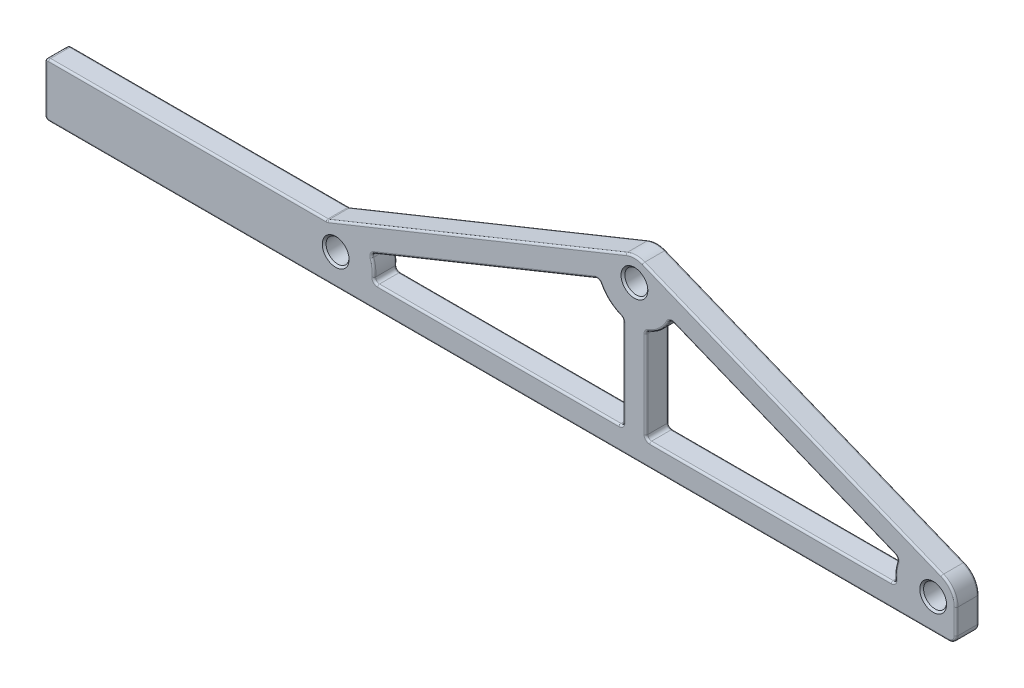
SolidWorks part; units mm, degrees
ref_plane "Plano frontal" through (0, 0, 0) normal (0, 0, 1) x (1, 0, 0)
ref_plane "Plano superior" through (0, 0, 0) normal (0, 1, 0) x (1, 0, 0)
ref_plane "Plano direito" through (0, 0, 0) normal (1, 0, 0) x (0, 0, -1)
sketch "Esboço1" plane through (0, 0, 0) normal (0, 0, 1) x (1, 0, 0)
  line L0 (-2.2496, 5.5623) -> (-80.2496, -25.9832)
  line L1 (2.2496, 5.5623) -> (80.2496, -25.9832)
  line L2 (84, -27.5) -> (-84, -27.5) construction
  line L3 (0, 0) -> (0, -27.5) construction
  line L4 (-78, -32) -> (78, -32) construction
  line L5 (0, -32) -> (0, -27.5) construction
  line L6 (-82, -40.0442) -> (-153.9281, -40.0442)
  line L7 (-82, -40.0442) -> (82, -40.0442)
  line L8 (84, -31.5455) -> (84, -38.0442)
  line L9 (-153.9281, -40.0442) -> (-153.9281, -25.9832)
  line L10 (-153.9281, -25.9832) -> (-80.2496, -25.9832)
  circle A0 centre (0, 0) radius 3
  arc A1 (2.2496, 5.5623) -> (-2.2496, 5.5623) centre (0, 0) ccw
  arc A2 (80.2496, -25.9832) -> (84, -31.5455) centre (78, -31.5455) cw
  arc A4 (82, -40.0442) -> (84, -38.0442) centre (82, -38.0442) ccw
  circle A6 centre (-78, -32) radius 3
  circle A7 centre (78, -32) radius 3
  point P20 (-84, -40.0442)
  dimension "D1" = 6
  dimension "D2" = 12
  dimension "D6" = 6
  dimension "D7" = 2
  dimension "D3" = 168
  dimension "D4" = 12.5442
  dimension "D5" = 27.5
  dimension "D8" = 32
  dimension "D9" = 156
extrude "Ressalto-extrusão1" add sketch "Esboço1" along normal mid plane 6
chamfer "Chanfro1" distance 0.5 angle 45 6 edges at (81, -32, -3) (81, -32, 3) (3, 0, -3) (3, 0, 3) (-75, -32, -3) (-75, -32, 3)
sketch "Esboço2" plane through (0, 0, 0) normal (0, 0, 1) x (1, 0, 0)
  line L0 (-2.2496, 5.5623) -> (-80.2496, -25.9832) construction
  line L1 (2.2496, 5.5623) -> (80.2496, -25.9832) construction
  line L2 (2.2496, 5.5623) -> (80.2496, -25.9832) construction
  line L3 (-2.2496, 5.5623) -> (-80.2496, -25.9832) construction
  line L4 (-82, -40.0442) -> (82, -40.0442) construction
  line L5 (-82, -40.0442) -> (82, -40.0442) construction
  line L6 (-82, -34.0442) -> (82, -34.0442)
  line L7 (0, 0) -> (-78, -31.5455)
  line L8 (0, 0) -> (78, -31.5455)
  line L9 (0, 0) -> (0, -47.2389) construction
  line L11 (-3, -40.8549) -> (3, -40.8549)
  line L12 (-3, -40.8549) -> (-3, -6.3841)
  line L13 (-3, -6.3841) -> (3, -6.3841)
  line L14 (3, -40.8549) -> (3, -6.3841)
  line L15 (-3, -40.8549) -> (3, -6.3841) construction
  line L16 (-3, -6.3841) -> (3, -40.8549) construction
  circle A0 centre (-78, -32) radius 10
  circle A1 centre (78, -32) radius 10
  circle A2 centre (0, 0) radius 10
  point P21 (0, -23.6195)
  dimension "D1" = 20
  dimension "D2" = 6
  dimension "D5" = 6
  dimension "D3" = 6
  dimension "D4" = 6
extrude "Corte-extrusão1" cut sketch "Esboço2" against normal mid plane 14 contours A2 L7 A0 L6 L12 | A2 L14 L6 A1 L8
fillet "Filete2" radius 1 13 edges at (3, -34.0442, 0) (-3, -34.0442, 0) (68.2112, -34.0442, 0) (68.8957, -27.8635, 0) (-9.2705, -3.7493, 0) (-3, -9.5394, 0) (9.2705, -3.7493, 0) (3, -9.5394, 0) (-68.8957, -27.8635, 0) (-68.2112, -34.0442, 0) (-153.9281, -40.0442, 0) (-153.9281, -25.9832, 0) (-80.2496, -25.9832, 0)
fillet "Filete1" radius 0.5 64 edges at (0, 6, -3) (41.2496, -10.2104, -3) (82.9748, -28.1912, -3) (84, -34.7949, -3) (83.4142, -39.4584, -3) (-35.464, -40.0442, -3) (0, 6, 3) (41.2496, -10.2104, 3) (82.9748, -28.1912, 3) (84, -34.7949, 3) (83.4142, -39.4584, 3) (-35.464, -40.0442, 3) (-41.1594, -10.174, -3) (-41.1594, -10.174, 3) (-3.2929, -33.7513, -3) (-3, -21.6456, -3) (-3.1743, -9.6829, -3) (-6.697, -7.4263, -3) (-9.4323, -4.0967, -3) (-39.0649, -15.799, -3) (-68.5096, -28.0035, -3) (-68.0699, -30.8197, -3) (-67.7896, -33.7169, -3) (3.1743, -9.6829, -3) (6.697, -7.4263, -3) (9.4323, -4.0967, -3) (39.0649, -15.799, -3) (68.5096, -28.0035, -3) (68.0699, -30.8197, -3) (67.7896, -33.7169, -3) (35.5248, -34.0442, -3) (3.2929, -33.7513, -3) (3.1743, -9.6829, 3) (6.697, -7.4263, 3) (9.4323, -4.0967, 3) (39.0649, -15.799, 3) (68.5096, -28.0035, 3) (68.0699, -30.8197, 3) (67.7896, -33.7169, 3) (35.5248, -34.0442, 3) (3.2929, -33.7513, 3) (-3.1743, -9.6829, 3) (-6.697, -7.4263, 3) (-9.4323, -4.0967, 3) (-39.0649, -15.799, 3) (-68.5096, -28.0035, 3) (-68.0699, -30.8197, 3) (-67.7896, -33.7169, 3) (-35.5248, -34.0442, 3) (-3.2929, -33.7513, 3) (-35.5248, -34.0442, -3) (3, -21.6456, -3) (3, -21.6456, 3) (-3, -21.6456, 3) (-153.6352, -39.7513, -3) (-153.9281, -33.0137, -3) (-153.6352, -39.7513, 3) (-153.9281, -33.0137, 3) (-153.6352, -26.2761, -3) (-116.6861, -25.9832, -3) (-80.2532, -25.9648, -3) (-153.6352, -26.2761, 3) (-116.6861, -25.9832, 3) (-80.2532, -25.9648, 3)
